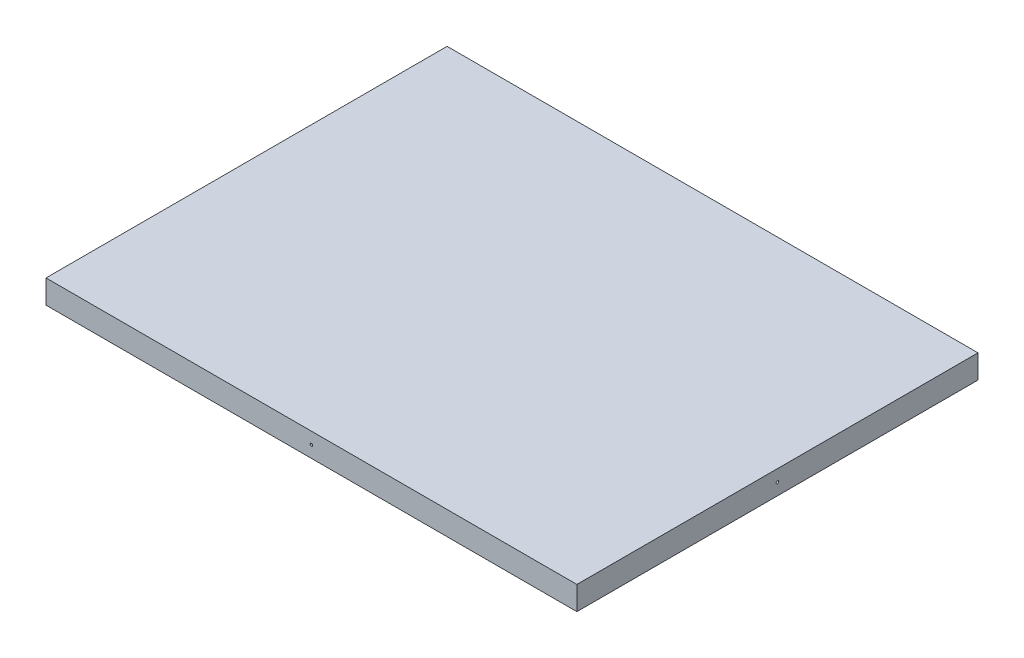
SolidWorks part; units mm, degrees
material "1.4511 (X3CrNb17)"
ref_plane "前视基准面" through (0, 0, 0) normal (0, 0, 1) x (1, 0, 0)
ref_plane "上视基准面" through (0, 0, 0) normal (0, 1, 0) x (1, 0, 0)
ref_plane "右视基准面" through (0, 0, 0) normal (1, 0, 0) x (0, 0, -1)
sketch "草图1" plane through (0, 0, 0) normal (0, 1, 0) x (1, 0, 0)
  line L1 (-450, 340) -> (450, 340)
  line L2 (-450, 340) -> (-450, -340)
  line L3 (-450, -340) -> (450, -340)
  line L4 (450, 340) -> (450, -340)
  line L5 (-450, 340) -> (450, -340) construction
  line L6 (-450, -340) -> (450, 340) construction
  point P0 (0, 0)
  dimension "D1" = 900
  dimension "D2" = 680
extrude "凸台-拉伸1" add sketch "草图1" along normal blind 40
sketch "草图2" plane through (0, 0, 340) normal (0, 0, 1) x (1, 0, 0)
  line L0 (-450, 40) -> (-450, 0) construction
  point P0 (0, 20)
  dimension "D1" = 450
hole_wizard "M5 螺纹孔1" positions "草图3" profile "草图4" tap size "M5" standard "GB" end condition through all
sketch "草图3" plane through (0, 0, 340) normal (0, 0, 1) x (1, 0, 0)
  point P0 (0, 20)
sketch "草图4" plane through (0, 20, 340) normal (1, 0, 0) x (0, -1, 0)
  line L0 (0, 0) -> (0, 680)
  line L1 (0, 680) -> (2.1, 680)
  line L2 (2.1, 680) -> (2.1, 0)
  line L5 (2.1, 0) -> (0, 0)
  line L11 (0, -6.35) -> (0, 107.95) construction
  dimension "通孔螺纹孔钻头直径" = 4.2
  dimension "通孔螺纹孔钻头深度" = 680
cosmetic thread "孔螺蚊线1" parameters "D2"=5
sketch "草图5" plane through (-450, 0, 0) normal (-1, 0, 0) x (0, 0, 1)
  line L0 (-340, 40) -> (-340, 0) construction
  point P0 (0, 20)
  dimension "D1" = 340
hole_wizard "M5 螺纹孔2" positions "草图6" profile "草图7" tap size "M5" standard "GB" end condition through all
sketch "草图6" plane through (-450, 0, 0) normal (-1, 0, 0) x (0, 0, 1)
  point P0 (0, 20)
sketch "草图7" plane through (-450, 20, 0) normal (0, 1, 0) x (0, 0, 1)
  line L0 (0, 0) -> (0, 900)
  line L1 (0, 900) -> (2.1, 900)
  line L2 (2.1, 900) -> (2.1, 0)
  line L5 (2.1, 0) -> (0, 0)
  line L11 (0, -6.35) -> (0, 107.95) construction
  dimension "通孔螺纹孔钻头直径" = 4.2
  dimension "通孔螺纹孔钻头深度" = 900
cosmetic thread "孔螺蚊线2" parameters "D2"=5
